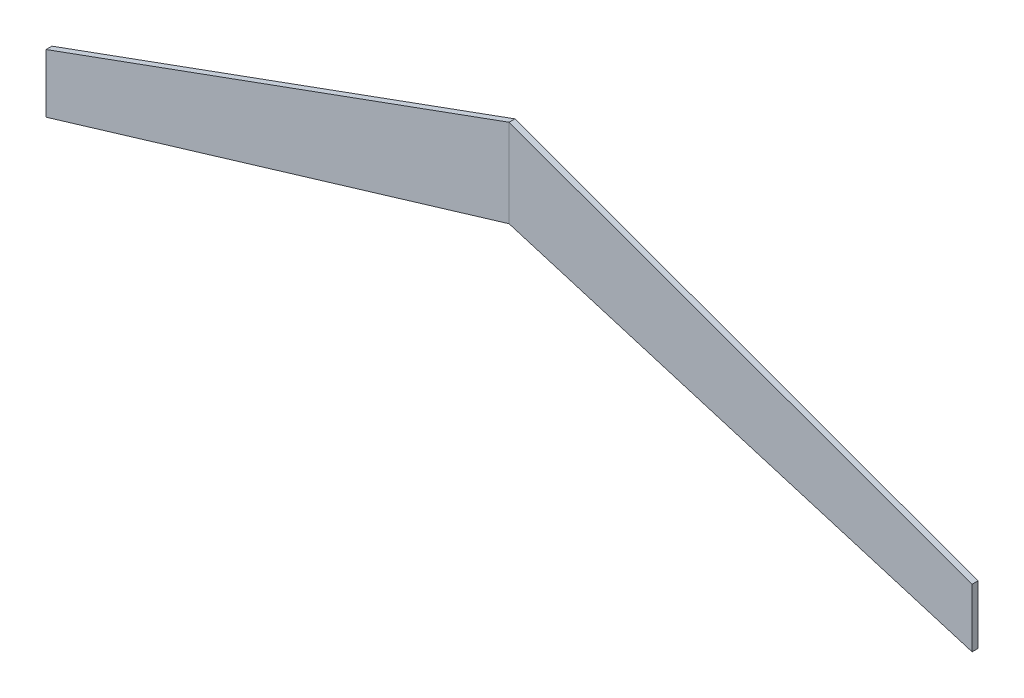
SolidWorks part; units mm, degrees
ref_plane "Ebene vorne" through (0, 0, 0) normal (0, 0, 1) x (1, 0, 0)
ref_plane "Ebene oben" through (0, 0, 0) normal (0, 1, 0) x (1, 0, 0)
ref_plane "Ebene rechts" through (0, 0, 0) normal (1, 0, 0) x (0, 0, -1)
sketch "Sketch1" plane through (0, 0, 0) normal (0, 0, 1) x (1, 0, 0)
  line L0 (0, 60) -> (0, 0)
  line L1 (316, -55.0146) -> (316, -95.0146)
  line L2 (316, -95.0146) -> (0, 0)
  line L3 (316, -55.0146) -> (0, 60)
  line L4 (0, 60) -> (142.7808, 60) construction
  dimension "D1" = 20
  dimension "D2" = 40
  dimension "D3" = 60
  dimension "D4" = 316
extrude "Boss-Extrude1" add sketch "Sketch1" along normal blind 4
mirror "Mirror1" about plane through (0, 0, 0) normal (1, 0, 0) of bodies 101
